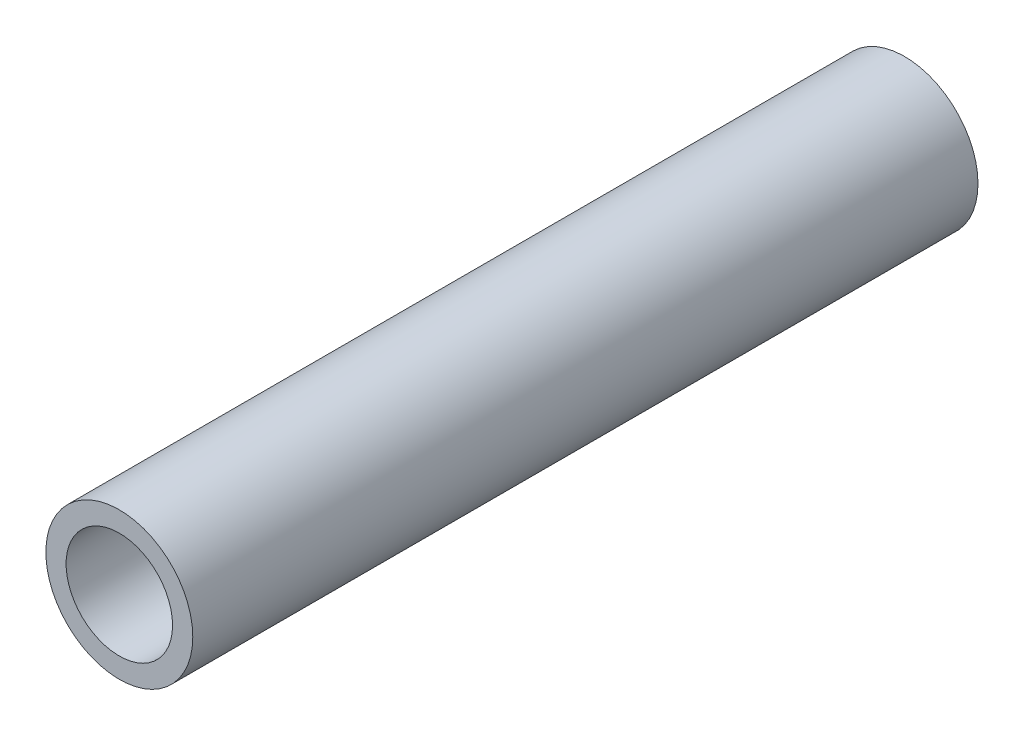
SolidWorks part; units mm, degrees
ref_plane "Front Plane" through (0, 0, 0) normal (0, 0, 1) x (1, 0, 0)
ref_plane "Top Plane" through (0, 0, 0) normal (0, 1, 0) x (1, 0, 0)
ref_plane "Right Plane" through (0, 0, 0) normal (1, 0, 0) x (0, 0, -1)
sketch "Sketch1" plane through (0, 0, 0) normal (0, 0, 1) x (1, 0, 0)
  circle A0 centre (0, 0) radius 10.6934
  circle A1 centre (0, 0) radius 7.747
  dimension "D1" = 21.3868
  dimension "D2" = 15.494
extrude "Boss-Extrude1" add sketch "Sketch1" along normal blind 114.3
